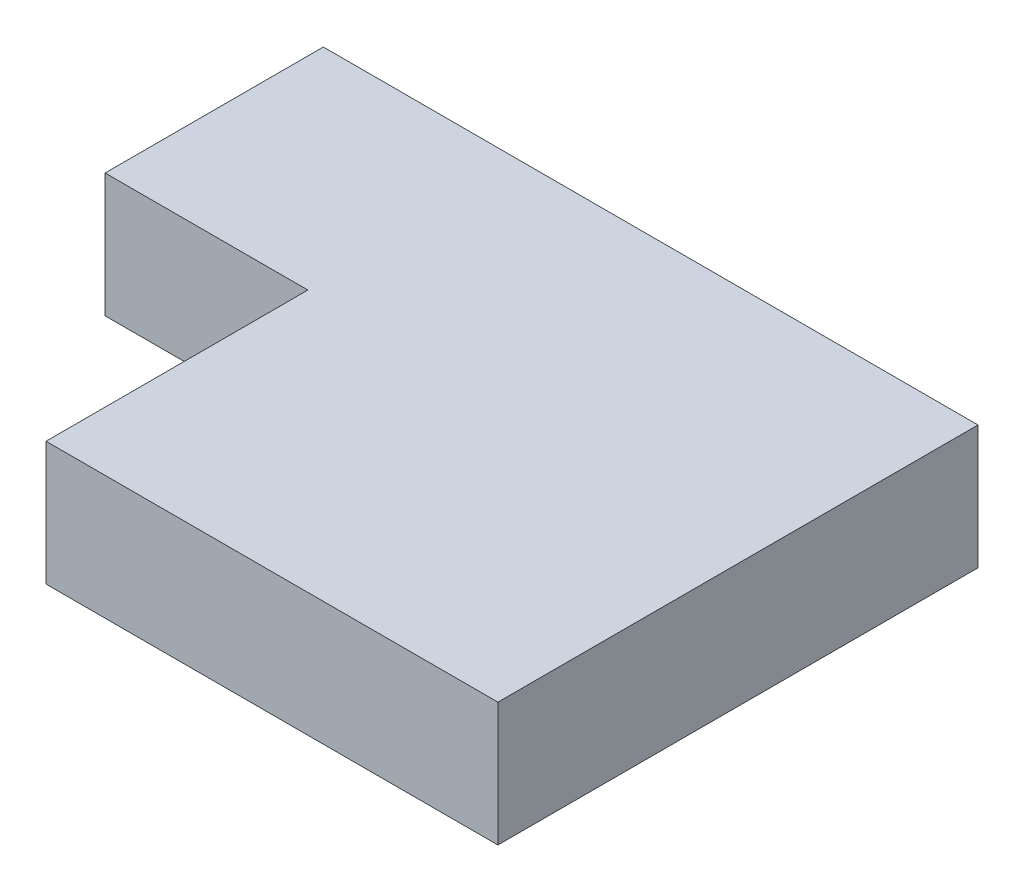
SolidWorks part; units mm, degrees
ref_plane "Front Plane" through (0, 0, 0) normal (0, 0, 1) x (1, 0, 0)
ref_plane "Top Plane" through (0, 0, 0) normal (0, 1, 0) x (1, 0, 0)
ref_plane "Right Plane" through (0, 0, 0) normal (1, 0, 0) x (0, 0, -1)
sketch "Sketch1" plane through (0, 0, 0) normal (0, 1, 0) x (1, 0, 0)
  line L1 (-91.9773, -36.0374) -> (-58.1106, -36.0374)
  line L2 (-91.9773, -36.0374) -> (-91.9773, -10.6374)
  line L3 (-91.9773, -10.6374) -> (-58.1106, -10.6374)
  line L4 (-58.1106, -36.0374) -> (-58.1106, -10.6374)
  line L5 (-91.9773, -36.0374) -> (-58.1106, -10.6374) construction
  line L6 (-91.9773, -10.6374) -> (-58.1106, -36.0374) construction
  point P4 (-75.044, -23.3374)
extrude "Boss-Extrude1" add sketch "Sketch1" along normal blind 4.8
sketch "Sketch3" plane through (0, 4.8, 0) normal (0, 1, 0) x (1, 0, 0)
  line L0 (-58.1106, -36.0374) -> (-75.644, -36.0374) construction
  line L1 (-91.9773, -36.0374) -> (-75.644, -36.0374)
  line L2 (-91.9773, -36.0374) -> (-91.9773, -19.104)
  line L3 (-91.9773, -19.104) -> (-75.644, -19.104)
  line L4 (-75.644, -36.0374) -> (-75.644, -19.104)
  line L5 (-91.9773, -36.0374) -> (-75.644, -19.104) construction
  line L6 (-91.9773, -19.104) -> (-75.644, -36.0374) construction
  line L11 (-89.8528, -10.6374) -> (-89.8528, -19.104) construction
  line L12 (-58.1106, -10.6374) -> (-91.9773, -10.6374) construction
  point P4 (-83.8106, -27.5707)
  dimension "D1" = 17.5333
extrude "Cut-Extrude1" cut sketch "Sketch3" against normal through all
sketch "Sketch4" plane through (0, 4.8, 0) normal (0, 1, 0) x (1, 0, 0)
  line L5 (-75.644, -19.104) -> (-75.644, -29.264)
  line L10 (-58.1106, -36.0374) -> (-58.1106, -10.6374) construction
  line L11 (-75.644, -29.264) -> (-58.1106, -29.264)
  line L13 (-75.644, -36.0374) -> (-75.644, -19.104) construction
  line L14 (-75.644, -29.264) -> (-75.644, -36.0374)
  line L15 (-75.644, -36.0374) -> (-58.1106, -36.0374)
  line L16 (-58.1106, -29.264) -> (-58.1106, -36.0374)
  line L17 (-75.644, -29.264) -> (-58.1106, -36.0374) construction
  line L18 (-75.644, -36.0374) -> (-58.1106, -29.264) construction
  line L19 (-75.644, -36.0374) -> (-58.1106, -36.0374) construction
  point P3 (-66.8773, -32.6507)
  line M3 (-91.9773, -10.6374) -> (-91.9773, -19.104)
  line M4 (-91.9773, -19.104) -> (-75.644, -19.104)
  line M5 (-75.644, -19.104) -> (-75.644, -36.0374)
  line M7 (-58.1106, -36.0374) -> (-58.1106, -10.6374)
  line M8 (-58.1106, -10.6374) -> (-91.9773, -10.6374)
  dimension "D1" = 10.16
extrude "Cut-Extrude3" cut sketch "Sketch4" against normal through all flip side to cut contours L11 M5 M7 M8 M3 M4
sketch "Sketch5" plane through (0, 0, 0) normal (0, -1, 0) x (1, 0, 0)
  line L0 (-75.644, 16.094) -> (-83.5106, 16.094)
  line L1 (-75.644, 29.264) -> (-75.644, 19.104) construction
  line L3 (-83.5106, 10.6374) -> (-91.9773, 10.6374)
  line L4 (-83.5106, 10.6374) -> (-83.5106, 19.104)
  line L5 (-83.5106, 19.104) -> (-91.9773, 19.104)
  line L6 (-91.9773, 10.6374) -> (-91.9773, 19.104)
  line L7 (-83.5106, 10.6374) -> (-91.9773, 19.104) construction
  line L8 (-83.5106, 19.104) -> (-91.9773, 10.6374) construction
  point P8 (-87.744, 14.8707)
  line M5 (-75.644, 19.104) -> (-91.9773, 19.104)
  line M6 (-91.9773, 19.104) -> (-91.9773, 10.6374)
  line M7 (-91.9773, 10.6374) -> (-58.1106, 10.6374)
  dimension "D1" = 8.4667
  dimension "D2" = 8.4667
extrude "Cut-Extrude4" cut sketch "Sketch5" against normal through all contours L4 M7 M5 M6
equation "\"MDF\"= 4.8mm"
equation "\"Foamcore\"= 4.6mm"
equation "\"PCB\" = 1.6mm"
equation "\"GMaterial\"= \"MDF\""
equation "\"D1@Boss-Extrude1\"=\"GMaterial\""
equation "\"BaseWidth\" = 10in"
equation "\"SkidLength\" = 1in"
equation "\"SkidClearance\" = 0.4in"
equation "\"MotorMountLength\" = 2in"
equation "\"MotorMountWidth\" = \"GMaterial\""
equation "\"MotorMountHeight\" = 2.25in"
equation "\"UnoStackWidth\" = 77.4mm"
equation "\"UnoStackLength\" = 79.8mm"
equation "\"UnoStackHeight\" = 34.2mm"
equation "\"TallHexRiserHeight\" = 22.2mm"
equation "\"PingPongBallSize\" = 40mm"
equation "\"BarrelLength\" = 9in"
equation "\"BarrelSize\" = \"PingPongBallSize\""
equation "\"PlatformLength\" = 4in"
equation "\"PlatformWidth\" = 6in"
equation "\"WheelWidth\"= 26mm"
equation "\"WheelDiameter\"=2.99213"
equation "\"ServoMountHeight\"=2.49223"
equation "\"ServoGearHeight\" = 0.95330261in"
equation "\"ServoMountLength\"= 1.53774"
equation "\"PivotHoleRadius\"= 0.616358"
equation "\"PlatformMountHeight\" = 3.19"
equation "\"TensionOffSet\"= .3mm"
equation "\"D1@Sketch3\"=\"TensionOffSet\"*2+2/3"
equation "\"D2@Sketch2\"=\"GMaterial\""
equation "\"MotorMountWedge\"=0.333333"
equation "\"D1@Sketch2\"=\"MotorMountWedge\""
equation "\"LaserCutterOffset\"= .3mm"
